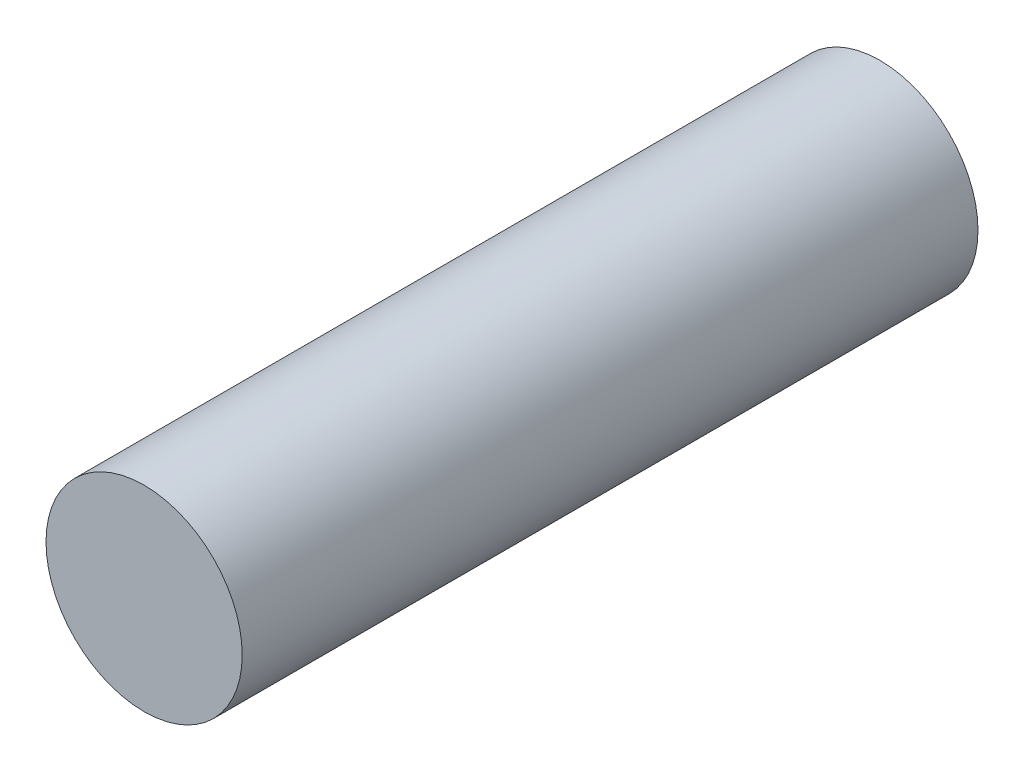
SolidWorks part; units mm, degrees
ref_plane "Plano frontal" through (0, 0, 0) normal (0, 0, 1) x (1, 0, 0)
ref_plane "Plano superior" through (0, 0, 0) normal (0, 1, 0) x (1, 0, 0)
ref_plane "Plano direito" through (0, 0, 0) normal (1, 0, 0) x (0, 0, -1)
sketch "Esboço1" plane through (0, 0, 0) normal (0, 0, 1) x (1, 0, 0)
  circle A0 centre (0, 0) radius 1
  dimension "D1" = 2
extrude "Ressalto-extrusão1" add sketch "Esboço1" along normal blind 7.5
